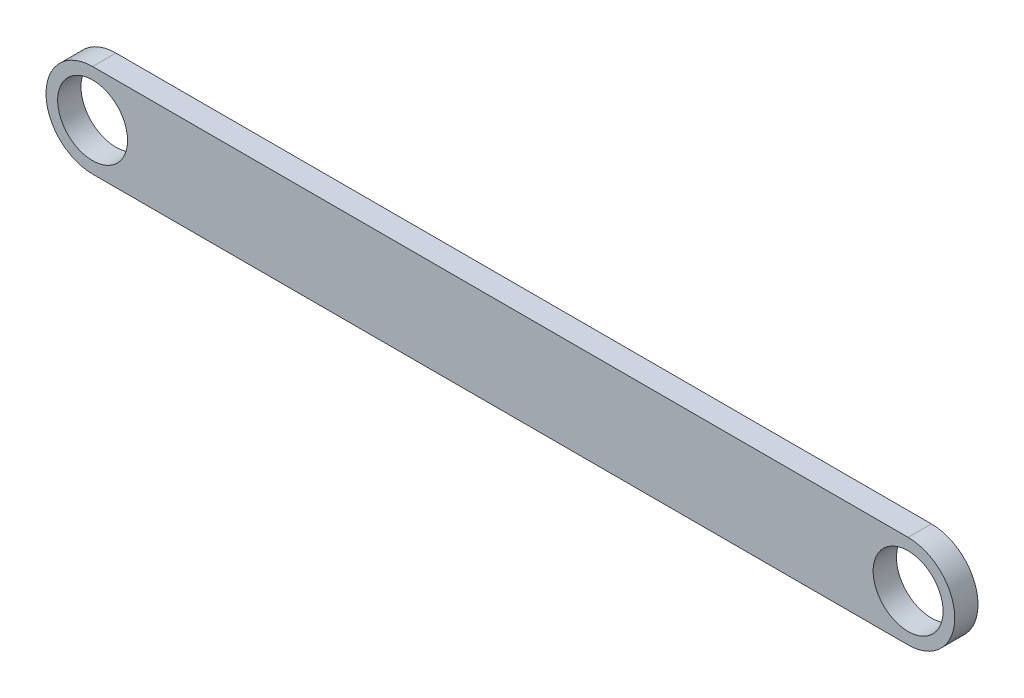
SolidWorks part; units mm, degrees
ref_plane "Front Plane" through (0, 0, 0) normal (0, 0, 1) x (1, 0, 0)
ref_plane "Top Plane" through (0, 0, 0) normal (0, 1, 0) x (1, 0, 0)
ref_plane "Right Plane" through (0, 0, 0) normal (1, 0, 0) x (0, 0, -1)
sketch "Sketch1" plane through (0, 0, 0) normal (0, 0, 1) x (1, 0, 0)
  line L0 (-62.548, 38.0032) -> (-27.548, 38.0032) construction
  line L1 (-62.548, 40.0032) -> (-27.548, 40.0032)
  line L2 (-62.548, 36.0032) -> (-27.548, 36.0032)
  arc A0 (-62.548, 40.0032) -> (-62.548, 36.0032) centre (-62.548, 38.0032) ccw
  arc A1 (-27.548, 36.0032) -> (-27.548, 40.0032) centre (-27.548, 38.0032) ccw
  circle A2 centre (-62.548, 38.0032) radius 1.5
  circle A3 centre (-27.548, 38.0032) radius 1.5
  point P2 (-45.048, 38.0032)
extrude "Boss-Extrude2" add sketch "Sketch1" along normal mid plane 1
